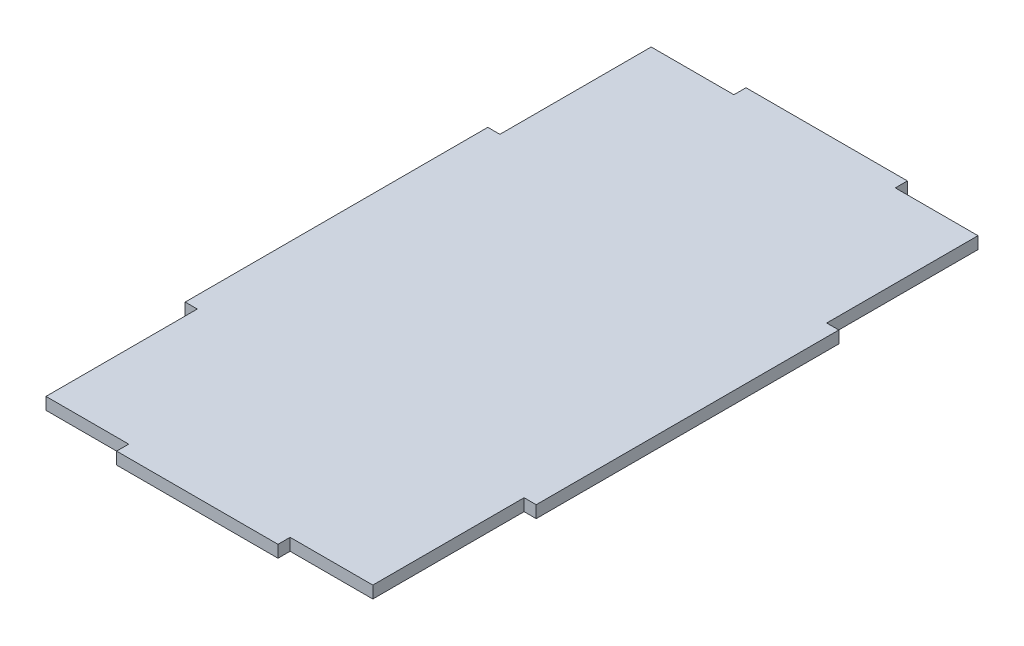
SolidWorks part; units mm, degrees
ref_plane "Alzado" through (0, 0, 0) normal (0, 0, 1) x (1, 0, 0)
ref_plane "Planta" through (0, 0, 0) normal (0, 1, 0) x (1, 0, 0)
ref_plane "Vista lateral" through (0, 0, 0) normal (1, 0, 0) x (0, 0, -1)
sketch "Croquis1" plane through (0, 0, 0) normal (0, 1, 0) x (1, 0, 0)
  line L0 (0, 112.5) -> (0, 150)
  line L1 (0, 0) -> (20.5, 0)
  line L2 (0, 0) -> (0, 37.5)
  line L3 (0, 150) -> (20.5, 150)
  line L4 (81, 0) -> (81, 37.5)
  line L5 (0, 37.5) -> (-3, 37.5)
  line L7 (0, 112.5) -> (-3, 112.5)
  line L8 (-3, 37.5) -> (-3, 112.5)
  line L9 (81, 37.5) -> (84, 37.5)
  line L11 (81, 112.5) -> (84, 112.5)
  line L12 (84, 37.5) -> (84, 112.5)
  line L14 (20.5, 0) -> (20.5, -3)
  line L15 (20.5, -3) -> (60.5, -3)
  line L16 (60.5, 0) -> (60.5, -3)
  line L18 (20.5, 150) -> (20.5, 153)
  line L19 (20.5, 153) -> (60.5, 153)
  line L20 (60.5, 150) -> (60.5, 153)
  line L21 (60.5, 150) -> (81, 150)
  line L22 (81, 112.5) -> (81, 150)
  line L23 (60.5, 0) -> (81, 0)
  dimension "D1" = 81
  dimension "D2" = 150
  dimension "D3" = 75
  dimension "D4" = 37.5
  dimension "D5" = 75
  dimension "D6" = 37.5
  dimension "D7" = 3
  dimension "D8" = 3
  dimension "D9" = 40
  dimension "D10" = 20.5
  dimension "D11" = 3
  dimension "D12" = 40
  dimension "D13" = 20.5
  dimension "D14" = 3
extrude "Saliente-Extruir1" add sketch "Croquis1" along normal blind 3
